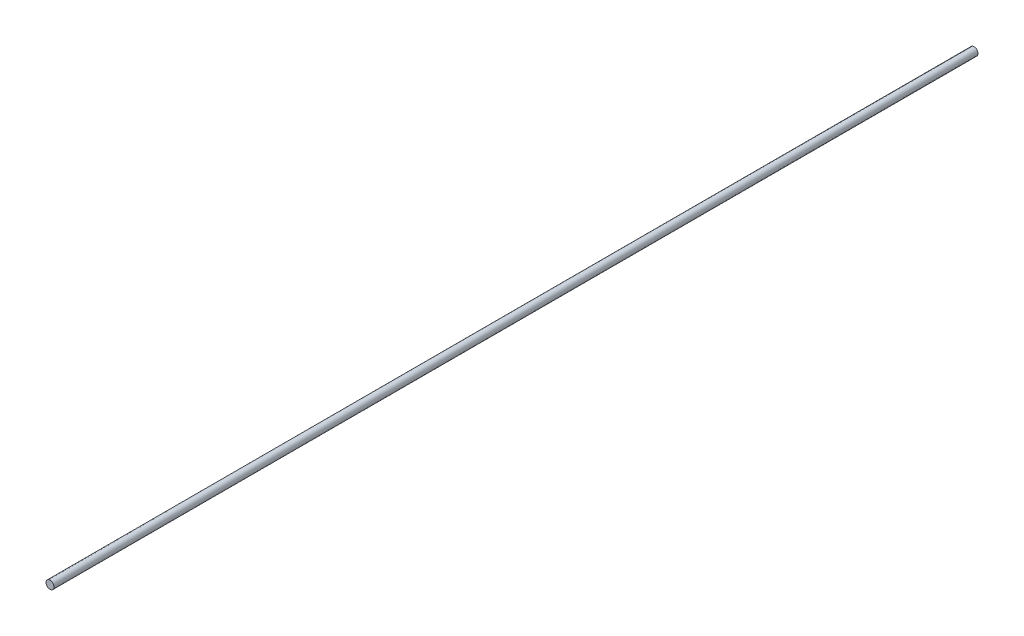
SolidWorks part; units mm, degrees
material "Material"
ref_plane "Front Plane" through (0, 0, 0) normal (0, 0, 1) x (1, 0, 0)
ref_plane "Top Plane" through (0, 0, 0) normal (0, 1, 0) x (1, 0, 0)
ref_plane "Right Plane" through (0, 0, 0) normal (1, 0, 0) x (0, 0, -1)
ref_plane "Plane1" through (0, 0, 0) normal (0, -1, 0) x (1, 0, 0)
sketch "Sketch1" plane through (0, 0, 0) normal (0, -1, 0) x (1, 0, 0)
  line L0 (1.5, 350) -> (0, 350)
  line L1 (0, 350) -> (0, 0)
  line L2 (0, 0) -> (1.5, 0)
  line L3 (1.5, 0) -> (1.5, 350)
  line L4 (0, 350) -> (0, 0) construction
revolve "Revolve1" add sketch "Sketch1" angle 360 about L4
